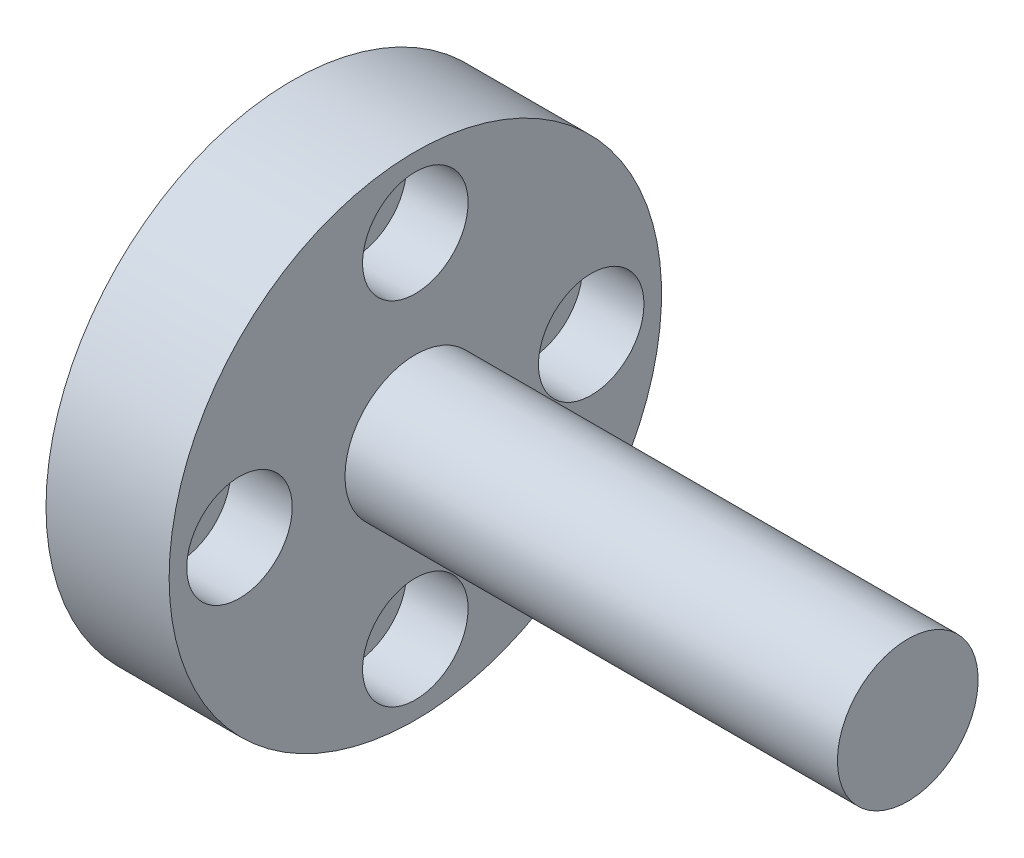
SolidWorks part; units mm, degrees
ref_plane "Front Plane" through (0, 0, 0) normal (0, 0, 1) x (1, 0, 0)
ref_plane "Top Plane" through (0, 0, 0) normal (0, 1, 0) x (1, 0, 0)
ref_plane "Right Plane" through (0, 0, 0) normal (1, 0, 0) x (0, 0, -1)
sketch "Sketch2" plane through (0, 0, 0) normal (0, 0, 1) x (1, 0, 0)
  line L0 (0, -14) -> (0, 14)
  line L1 (0, 14) -> (7, 14)
  line L2 (7, 14) -> (7, 4)
  line L3 (7, 4) -> (35, 4)
  line L4 (35, 4) -> (35, -4)
  line L5 (35, -4) -> (7, -4)
  line L6 (7, -4) -> (7, -14)
  line L7 (7, -14) -> (0, -14)
  line L8 (0, 0) -> (35, 0)
  point P4 (0, 0)
  point P10 (35, 0)
  dimension "D1" = 35
  dimension "D2" = 28
  dimension "D3" = 28
  dimension "D4" = 8
revolve "Revolve2" add sketch "Sketch2" angle 360 about L8
sketch "Sketch3" plane through (7, 0, 0) normal (1, 0, 0) x (0, 0, -1)
  line L0 (0, 0) -> (10, 0) construction
  circle A0 centre (0, 0) radius 10 construction
  point P4 (10, 0)
  dimension "D1" = 20
hole_wizard "CBORE for M3 SBHCS1" positions "Sketch3" profile "Sketch4" counterbore size "M3" standard "ANSI Metric" end condition through all
sketch "Sketch4" plane through (7, 0, -10) normal (0, 1, 0) x (0, 0, -1)
  line L0 (0, 0) -> (0, 7)
  line L1 (0, 7) -> (1.6, 7)
  line L3 (1.6, 7) -> (1.6, 3.5)
  line L4 (1.6, 3.5) -> (3, 3.5)
  line L5 (3, 3.5) -> (3, 0)
  line L7 (3, 0) -> (0, 0)
  line L11 (0, -6.35) -> (0, 107.95) construction
  dimension "Thru Hole Dia." = 3.2
  dimension "Thru Hole Depth" = 7
  dimension "C'Bore Dia." = 6
  dimension "C'Bore Depth" = 3.5
pattern_circular "CirPattern1" count 4 over 360 about axis through (0, 0, 0) along (1, 0, 0) of "CBORE for M3 SBHCS1"
sketch "Sketch5" plane through (0, 0, 0) normal (-1, 0, 0) x (0, 0, 1)
  circle A0 centre (0, 0) radius 2.5
  dimension "D1" = 5
extrude "Cut-Extrude1" cut sketch "Sketch5" against normal blind 2
